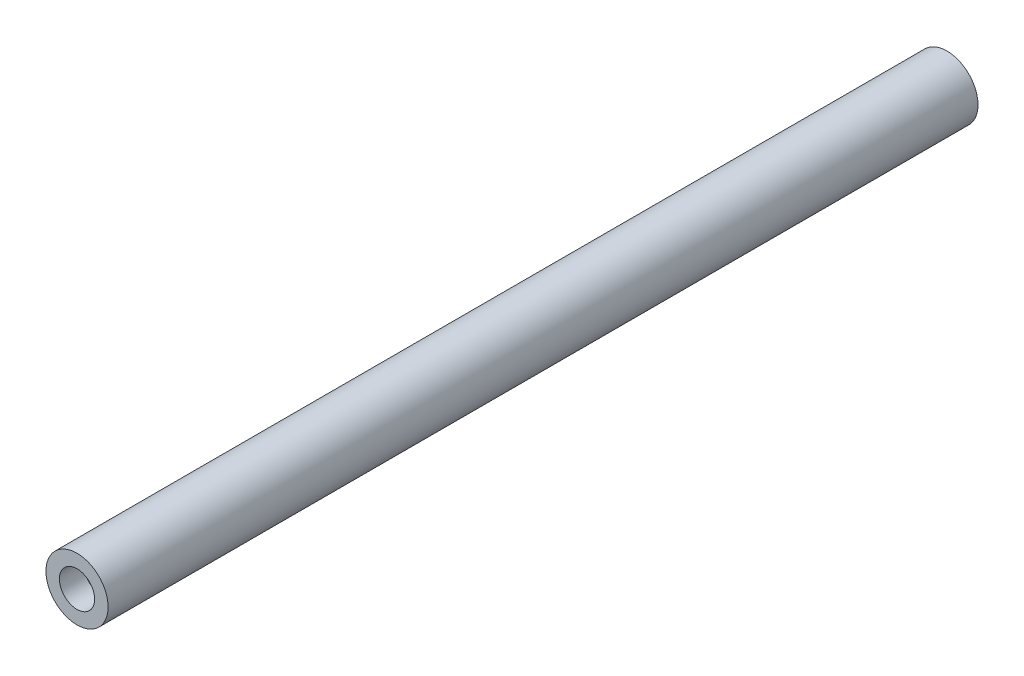
SolidWorks part; units mm, degrees
material "ABS"
ref_plane "Plan de face" through (0, 0, 0) normal (0, 0, 1) x (1, 0, 0)
ref_plane "Plan de dessus" through (0, 0, 0) normal (0, 1, 0) x (1, 0, 0)
ref_plane "Plan de droite" through (0, 0, 0) normal (1, 0, 0) x (0, 0, -1)
sketch "Esquisse1" plane through (0, 0, 0) normal (0, 0, 1) x (1, 0, 0)
  circle A0 centre (0, 0) radius 6.35
  dimension "D1" = 12.7
extrude "Boss.-Extru.1" add sketch "Esquisse1" against normal blind 177.8
sketch "Esquisse2" plane through (0, 0, 0) normal (0, 0, 1) x (1, 0, 0)
  circle A0 centre (0, 0) radius 3.6
  dimension "D1" = 7.2
extrude "Enlèv. mat.-Extru.1" cut sketch "Esquisse2" against normal blind 5
